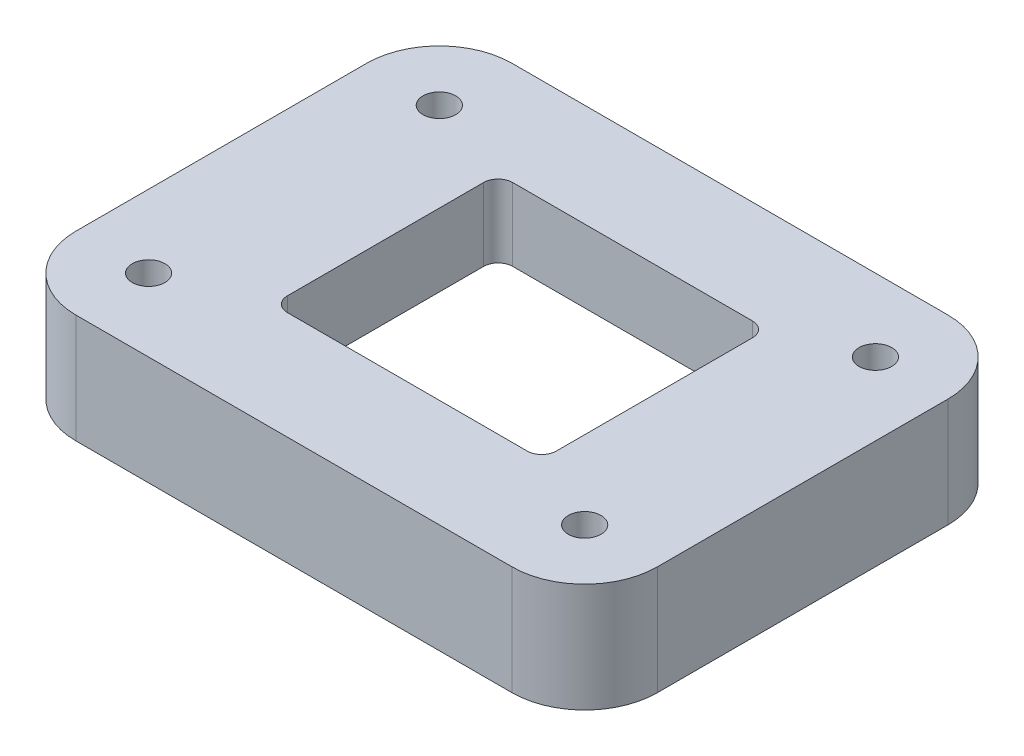
SolidWorks part; units mm, degrees
ref_plane "Plan de face" through (0, 0, 0) normal (0, 0, 1) x (1, 0, 0)
ref_plane "Plan de dessus" through (0, 0, 0) normal (0, 1, 0) x (1, 0, 0)
ref_plane "Plan de droite" through (0, 0, 0) normal (1, 0, 0) x (0, 0, -1)
sketch "Esquisse1" plane through (0, 0, 0) normal (0, 1, 0) x (1, 0, 0)
  line L0 (10, -10) -> (70, -50) construction
  line L1 (10, 0) -> (70, 0)
  line L2 (0, -10) -> (0, -50)
  line L3 (10, -60) -> (70, -60)
  line L4 (80, -10) -> (80, -50)
  line L5 (24.2538, -14.1572) -> (57.2538, -14.1572)
  line L6 (22.2538, -16.1572) -> (22.2538, -43.1572)
  line L7 (24.2538, -45.1572) -> (57.2538, -45.1572)
  line L8 (59.2538, -16.1572) -> (59.2538, -43.1572)
  line L9 (70, -10) -> (10, -50) construction
  arc A0 (0, -50) -> (10, -60) centre (10, -50) ccw
  arc A1 (80, -50) -> (70, -60) centre (70, -50) cw
  arc A2 (0, -10) -> (10, 0) centre (10, -10) cw
  arc A3 (70, 0) -> (80, -10) centre (70, -10) cw
  circle A4 centre (10, -10) radius 2.25
  circle A5 centre (70, -10) radius 2.25
  circle A6 centre (10, -50) radius 2.25
  circle A7 centre (70, -50) radius 2.25
  arc A8 (24.2538, -45.1572) -> (22.2538, -43.1572) centre (24.2538, -43.1572) cw
  arc A9 (57.2538, -45.1572) -> (59.2538, -43.1572) centre (57.2538, -43.1572) ccw
  arc A10 (59.2538, -16.1572) -> (57.2538, -14.1572) centre (57.2538, -16.1572) ccw
  arc A11 (22.2538, -16.1572) -> (24.2538, -14.1572) centre (24.2538, -16.1572) cw
  point P9 (80, -60)
  point P12 (0, 0)
  point P15 (80, 0)
  point P29 (59.2538, -45.1572)
  point P32 (59.2538, -14.1572)
  point P35 (22.2538, -14.1572)
  dimension "D3" = 10
  dimension "D4" = 37
  dimension "D6" = 2
  dimension "D7" = 4.5
  dimension "D1" = 80
  dimension "D2" = 60
  dimension "D5" = 31
extrude "Boss.-Extru.1" add sketch "Esquisse1" along normal blind 15
sketch "Esquisse2" plane through (0, 0, 0) normal (0, -1, 0) x (1, 0, 0)
  line L0 (70, 0) -> (10, 0) construction
  line L1 (8, 57) -> (72, 57)
  line L2 (3, 52) -> (3, 8)
  line L3 (8, 3) -> (72, 3)
  line L4 (77, 52) -> (77, 8)
  line L5 (10, 60) -> (70, 60) construction
  line L6 (80, 50) -> (80, 10) construction
  line L7 (0, 10) -> (0, 50) construction
  arc A0 (3, 52) -> (8, 57) centre (8, 52) cw
  arc A1 (3, 8) -> (8, 3) centre (8, 8) ccw
  arc A2 (72, 3) -> (77, 8) centre (72, 8) ccw
  arc A3 (77, 52) -> (72, 57) centre (72, 52) ccw
  dimension "D5" = 5
  dimension "D1" = 3
  dimension "D2" = 3
  dimension "D3" = 3
  dimension "D4" = 3
extrude "Enlèv. mat.-Extru.1" cut sketch "Esquisse2" against normal blind 5
